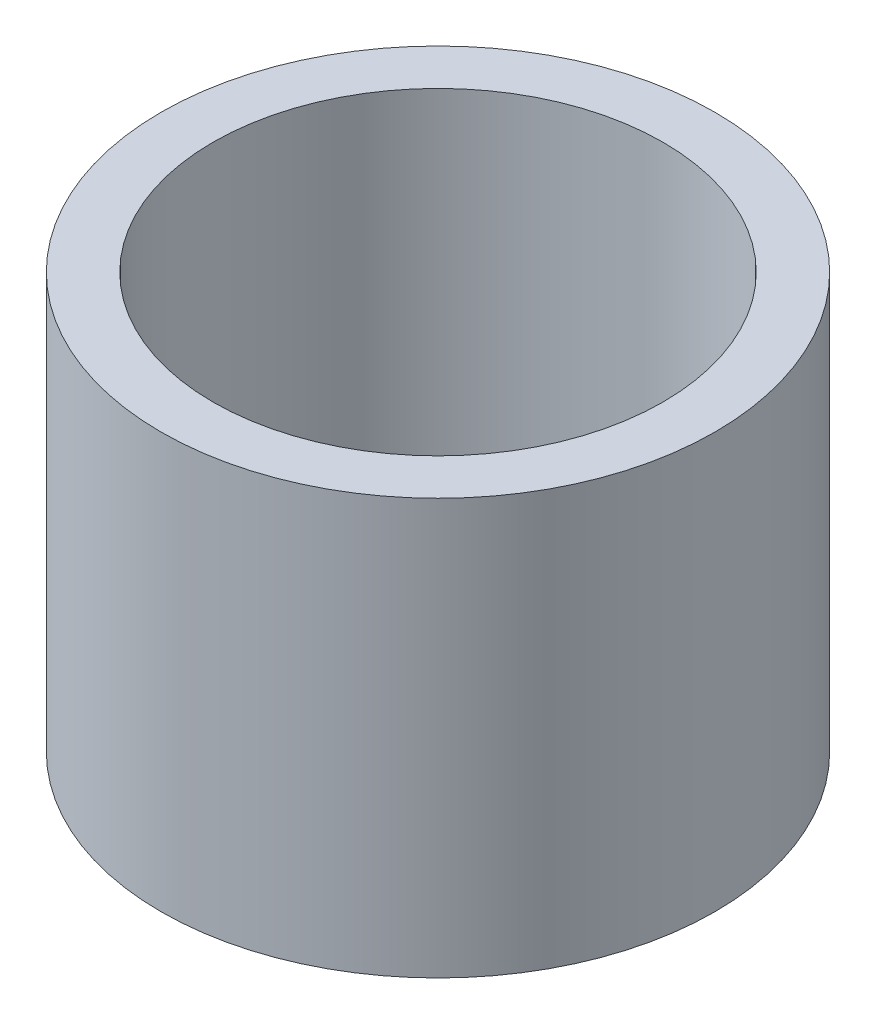
SolidWorks part; units mm, degrees
material "Commercial Bronze, UNS C22000 (90-10 Bronze)"
ref_plane "Front Plane" through (0, 0, 0) normal (0, 0, 1) x (1, 0, 0)
ref_plane "Top Plane" through (0, 0, 0) normal (0, 1, 0) x (1, 0, 0)
ref_plane "Right Plane" through (0, 0, 0) normal (1, 0, 0) x (0, 0, -1)
sketch "Sketch1" plane through (0, 0, 0) normal (0, 1, 0) x (1, 0, 0)
  circle A0 centre (0, 0) radius 10.3187
  circle A1 centre (0, 0) radius 12.7
  dimension "D1" = 20.6375
extrude "Boss-Extrude1" add sketch "Sketch1" along normal blind 19.05
